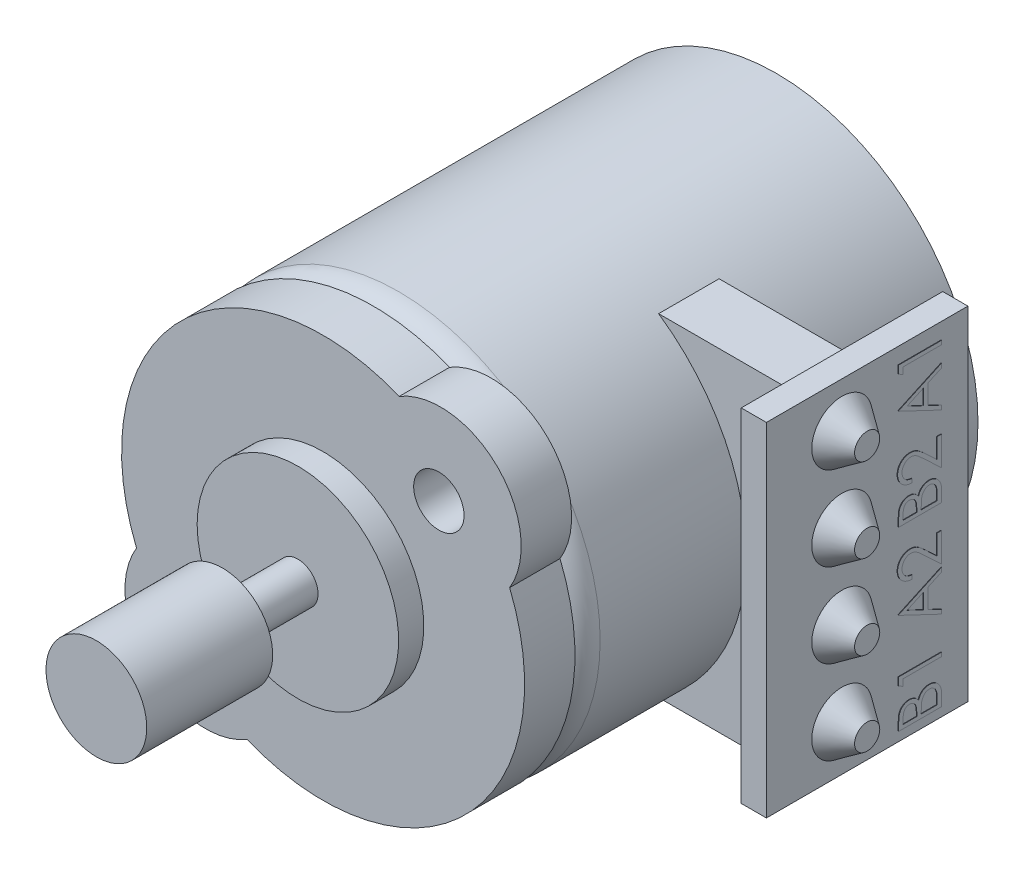
SolidWorks part; units mm, degrees
ref_plane "Front" through (0, 0, 0) normal (0, 0, 1) x (1, 0, 0)
ref_plane "Top" through (0, 0, 0) normal (0, 1, 0) x (1, 0, 0)
ref_plane "Right" through (0, 0, 0) normal (1, 0, 0) x (0, 0, -1)
sketch "Эскиз2" plane through (0, 0, 0) normal (0, 1, 0) x (1, 0, 0)
  line L0 (0, 0) -> (0, -15.4747) construction
  line L1 (0, 0) -> (-3.5, 0)
  line L2 (-3.5, 0) -> (-3.5, -0.2)
  line L3 (-3.5, -0.2) -> (-4, -0.2)
  line L4 (-4, -0.2) -> (-4, -7.7)
  line L7 (-2, -9.7) -> (-0.4, -9.7)
  line L8 (-0.4, -9.7) -> (-0.4, -11.2)
  line L9 (-0.4, -11.2) -> (-1, -11.2)
  line L10 (-1, -11.2) -> (-1, -13.7)
  line L11 (-1, -13.7) -> (0, -13.7)
  line L12 (0, -13.7) -> (0, 0)
  line L13 (-2, -9.7) -> (-2, -9.2)
  line L14 (-2, -9.2) -> (-4, -9.2)
  line L15 (-4, -9.2) -> (-4, -8.2)
  line L16 (-4, -8.2) -> (-3.5, -8.2)
  arc A0 (-4, -7.7) -> (-3.5, -8.2) centre (-3.5, -7.7) ccw
  point P9 (-0.5, -13.7)
  dimension "D4" = 9.7
  dimension "D11" = 0.5
  dimension "D1" = 8
  dimension "D2" = 0.5
  dimension "D3" = 0.2
  dimension "D5" = 0.5
  dimension "D6" = 1
  dimension "D7" = 9.2
  dimension "D8" = 4
  dimension "D9" = 0.8
  dimension "D10" = 2
  dimension "D12" = 4
  dimension "D13" = 2.5
revolve "Повернуть1" add sketch "Эскиз2" angle 360 about L0
sketch "Эскиз7" plane through (0, 0, 9.2) normal (0, 0, 1) x (1, 0, 0)
  line L0 (3.4648, 3.4648) -> (-3.4648, -3.4648) construction
  line L1 (0, 0) -> (0, 2.6929) construction
  arc A0 (3.7035, 1.5114) -> (1.5114, 3.7035) centre (2.3356, 2.3356) ccw
  circle A1 centre (0, 0) radius 4 construction
  arc A2 (-1.5114, -3.7035) -> (-3.7035, -1.5114) centre (-2.3356, -2.3356) cw
  arc A3 (-1.5114, -3.7035) -> (-3.7035, -1.5114) centre (0, 0) cw
  arc A4 (3.7035, 1.5114) -> (1.5114, 3.7035) centre (0, 0) ccw
  point P2 (0, 0)
  point P16 (-3.4648, -3.4648)
  dimension "D1" = 9.8
  dimension "D2" = 3.1
  dimension "D3" = 45
extrude "Бобышка-Вытянуть5" add sketch "Эскиз7" against normal up to surface (1 mm away) up to face at (-4, 0, 8.2)
sketch "Эскиз8" plane through (0, 0, 9.2) normal (0, 0, 1) x (1, 0, 0)
  line L0 (-2.2981, -2.2981) -> (2.2981, 2.2981) construction
  line L1 (3.4648, 3.4648) -> (-3.4648, -3.4648) construction
  circle A0 centre (-2.2981, -2.2981) radius 0.5
  circle A1 centre (2.2981, 2.2981) radius 0.5
  point P6 (0, 0)
  dimension "D1" = 1
  dimension "D2" = 6.5
extrude "Вырез-Вытянуть1" cut sketch "Эскиз8" against normal up to surface (1 mm away)
sketch "Эскиз3" plane through (0, 0, 0) normal (1, 0, 0) x (0, 0, -1)
  line L0 (-4.2, 0) -> (0, 0) construction
  line L1 (-4.8, 3.3) -> (-3.6, 3.3)
  line L2 (-4.8, 3.3) -> (-4.8, -3.3)
  line L3 (-4.8, -3.3) -> (-3.6, -3.3)
  line L4 (-3.6, 3.3) -> (-3.6, -3.3)
  line L5 (-4.8, 3.3) -> (-3.6, -3.3) construction
  line L6 (-4.8, -3.3) -> (-3.6, 3.3) construction
  point P4 (-4.2, 0)
  dimension "D1" = 3.6
  dimension "D2" = 1.2
  dimension "D3" = 6.6
extrude "Бобышка-Вытянуть1" add sketch "Эскиз3" along normal blind 4.8
sketch "Эскиз4" plane through (4.8, 0, 0) normal (1, 0, 0) x (0, 0, -1)
  line L1 (-1.7, -3.4) -> (-5.7, -3.4)
  line L2 (-1.7, -3.4) -> (-1.7, 3.4)
  line L3 (-1.7, 3.4) -> (-5.7, 3.4)
  line L4 (-5.7, -3.4) -> (-5.7, 3.4)
  line L5 (-1.7, -3.4) -> (-5.7, 3.4) construction
  line L6 (-1.7, 3.4) -> (-5.7, -3.4) construction
  line L9 (-9.2, 4) -> (-9.2, -4) construction
  line L10 (-3.7, 0) -> (0, 0) construction
  line L11 (-4.8, -3.3) -> (-3.6, -3.3) construction
  point P0 (-3.7, 0)
  dimension "D1" = 4
  dimension "D2" = 3.5
  dimension "D3" = 0.1
extrude "Бобышка-Вытянуть2" add sketch "Эскиз4" along normal blind 0.5
sketch "Эскиз5" plane through (5.3, 0, 0) normal (1, 0, 0) x (0, 0, -1)
  line L0 (-4.2, -3.4) -> (-4.2, -2.5) construction
  line L1 (-5.7, -3.4) -> (-1.7, -3.4) construction
  line L2 (-4.2, -2.5) -> (-4.2, -0.8333) construction
  line L3 (-4.2, -0.8333) -> (-4.2, 0.8333) construction
  line L4 (-4.2, 0.8333) -> (-4.2, 2.5) construction
  line L5 (-4.2, 2.5) -> (-4.2, 3.4) construction
  line L6 (-1.7, 3.4) -> (-5.7, 3.4) construction
  circle A0 centre (-4.2, -2.5) radius 0.6
  circle A1 centre (-4.2, -0.8333) radius 0.6
  circle A2 centre (-4.2, 0.8333) radius 0.6
  circle A3 centre (-4.2, 2.5) radius 0.6
  dimension "D1" = 1.2
  dimension "D2" = 5
extrude "Бобышка-Вытянуть3" add sketch "Эскиз5" along normal blind 0.5 draft 35
sketch "Эскиз6" plane through (5.3, 0, 0) normal (1, 0, 0) x (0, 0, 1)
  line L0 (2.2334, -3.4) -> (2.2334, 3.4) construction
  line L6 (1.7, -3.4) -> (5.7, -3.4) construction
  line L7 (5.7, 3.4) -> (1.7, 3.4) construction
  text T0 "B1 A2 B2 A1" font "Century Gothic" height 0.85
extrude "Бобышка-Вытянуть4" add sketch "Эскиз6" along normal blind 0.01
